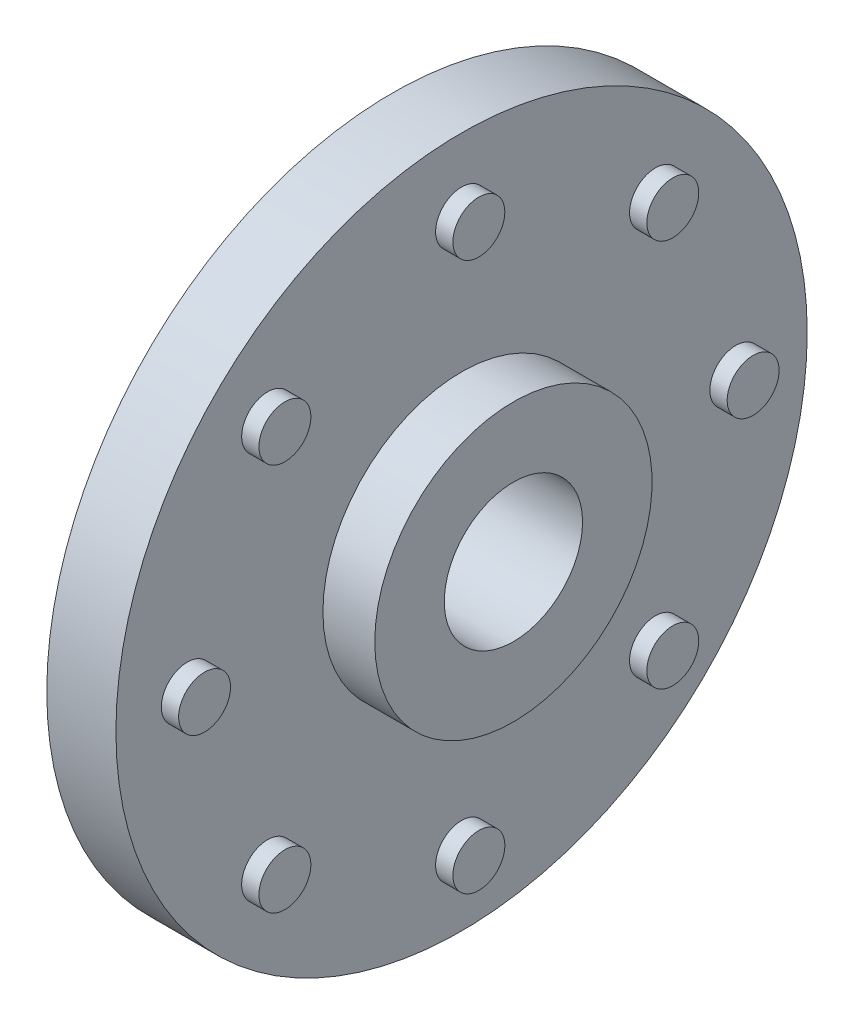
SolidWorks part; units mm, degrees
ref_plane "Front Plane" through (0, 0, 0) normal (0, 0, 1) x (1, 0, 0)
ref_plane "Top Plane" through (0, 0, 0) normal (0, 1, 0) x (1, 0, 0)
ref_plane "Right Plane" through (0, 0, 0) normal (1, 0, 0) x (0, 0, -1)
sketch "Sketch1" plane through (0, 0, 0) normal (1, 0, 0) x (0, 0, -1)
  circle A0 centre (0, 0) radius 127
  dimension "D1" = 254
extrude "Boss-Extrude1" add sketch "Sketch1" along normal blind 25.4
sketch "Sketch2" plane through (25.4, 0, 0) normal (1, 0, 0) x (0, 0, -1)
  circle A0 centre (0, 0) radius 99.2248 construction
  circle A1 centre (0, 100.2088) radius 9.5416
extrude "Boss-Extrude2" add sketch "Sketch2" along normal blind 6.35
pattern_circular "CirPattern1" count 8 over 360 about axis through (0, -0.5688, 0) along (1, 0, 0) of "Boss-Extrude2"
sketch "Sketch3" plane through (25.4, 0, 0) normal (1, 0, 0) x (0, 0, -1)
  circle A0 centre (0, 0) radius 50.9442
extrude "Boss-Extrude3" add sketch "Sketch3" along normal blind 19.05
sketch "Sketch4" plane through (44.45, 0, 0) normal (1, 0, 0) x (0, 0, -1)
  circle A0 centre (0, 0) radius 25.4
  dimension "D1" = 50.8
extrude "Cut-Extrude1" cut sketch "Sketch4" against normal blind 132.334
